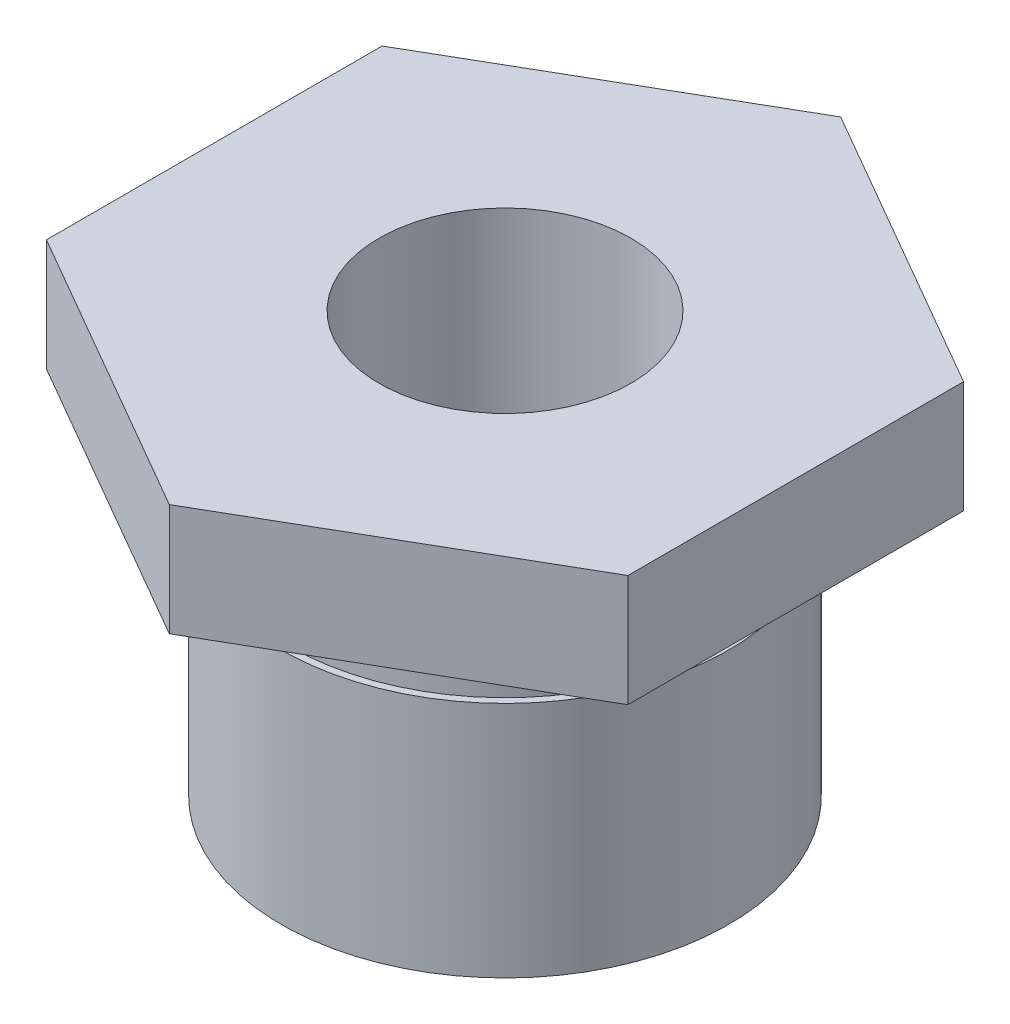
SolidWorks part; units mm, degrees
ref_plane "Front Plane" through (0, 0, 0) normal (0, 0, 1) x (1, 0, 0)
ref_plane "Top Plane" through (0, 0, 0) normal (0, 1, 0) x (1, 0, 0)
ref_plane "Right Plane" through (0, 0, 0) normal (1, 0, 0) x (0, 0, -1)
sketch "Sketch1" plane through (0, 0, 0) normal (0, 0, 1) x (1, 0, 0)
  line L0 (0, 0) -> (0, 34.5304) construction
  line L1 (-9, 66.9976) -> (-24, 66.9976)
  line L2 (-24, 66.9976) -> (-24, 58.9976)
  line L3 (-24, 58.9976) -> (-15.5, 58.9976)
  line L4 (-15.5, 58.9976) -> (-15.5, 53.9976)
  line L5 (-15.5, 53.9976) -> (-16, 53.9976)
  line L6 (-16, 53.9976) -> (-16, 36.9976)
  line L7 (-16, 36.9976) -> (-9, 36.9976)
  line L8 (-9, 36.9976) -> (-9, 66.9976)
  dimension "D1" = 18
  dimension "D2" = 48
  dimension "D3" = 32
  dimension "D4" = 31
  dimension "D5" = 17
  dimension "D6" = 22
  dimension "D7" = 30
revolve "Revolve1" add sketch "Sketch1" angle 360 about L0
sketch "Sketch2" plane through (0, 66.9976, 0) normal (0, 1, 0) x (-1, 0, 0)
  line L1 (0, -24) -> (20.7846, -12)
  line L2 (20.7846, -12) -> (20.7846, 12)
  line L3 (20.7846, 12) -> (0, 24)
  line L4 (0, 24) -> (-20.7846, 12)
  line L5 (-20.7846, 12) -> (-20.7846, -12)
  line L6 (-20.7846, -12) -> (0, -24)
  circle A0 centre (0, 0) radius 20.7846 construction
  circle A1 centre (0, 0) radius 28.8557
  dimension "D1" = 48
extrude "Cut-Extrude1" cut sketch "Sketch2" against normal blind 10
